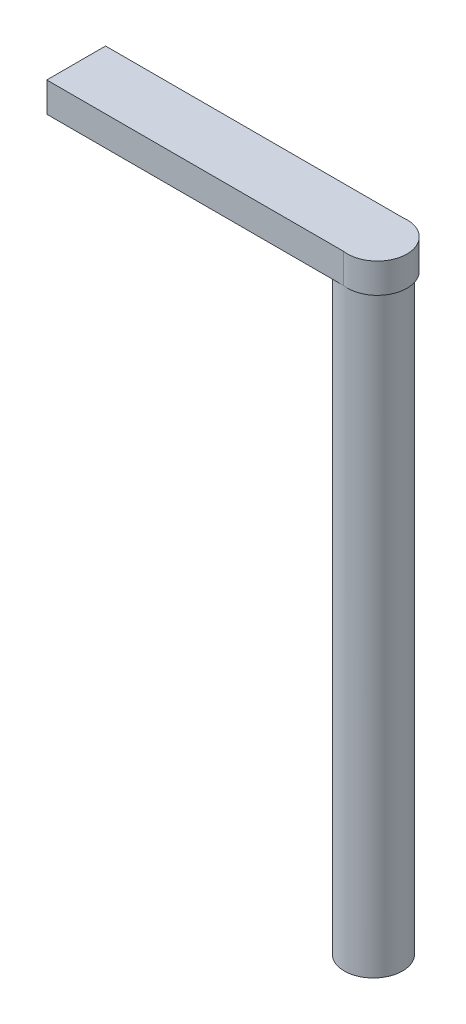
SolidWorks part; units mm, degrees
ref_plane "Front Plane" through (0, 0, 0) normal (0, 0, 1) x (1, 0, 0)
ref_plane "Top Plane" through (0, 0, 0) normal (0, 1, 0) x (1, 0, 0)
ref_plane "Right Plane" through (0, 0, 0) normal (1, 0, 0) x (0, 0, -1)
sketch "Sketch1" plane through (0, 0, 0) normal (0, 1, 0) x (1, 0, 0)
  circle A0 centre (0, 0) radius 4.9
  dimension "D1" = 9.8
extrude "Boss-Extrude1" add sketch "Sketch1" along normal blind 100
sketch "Sketch2" plane through (0, 100, 0) normal (0, 1, 0) x (1, 0, 0)
  line L1 (0, 4.9) -> (-50, 4.9)
  line L3 (0, -5) -> (-50, -5)
  line L4 (-50, 4.9) -> (-50, -5)
  circle A0 centre (0, 0) radius 4.9 construction
  arc A1 (0, -5) -> (0, 4.9) centre (0.7053, -0.05) ccw
  dimension "D1" = 50
extrude "Boss-Extrude2" add sketch "Sketch2" along normal blind 5
